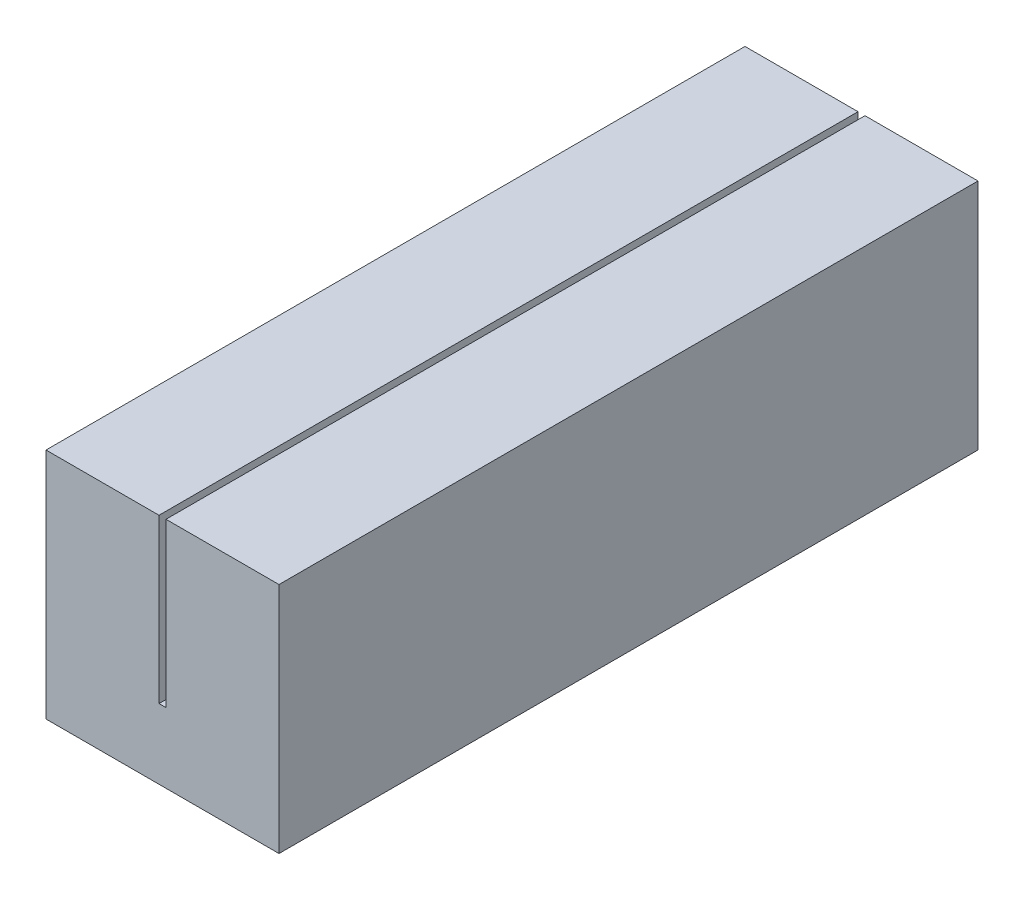
SolidWorks part; units mm, degrees
ref_plane "Front Plane" through (0, 0, 0) normal (0, 0, 1) x (1, 0, 0)
ref_plane "Top Plane" through (0, 0, 0) normal (0, 1, 0) x (1, 0, 0)
ref_plane "Right Plane" through (0, 0, 0) normal (1, 0, 0) x (0, 0, -1)
sketch "Sketch1" plane through (0, 0, 0) normal (0, 0, 1) x (1, 0, 0)
  line L0 (-0.15, 5) -> (-0.15, -2)
  line L1 (-5, 5) -> (-0.15, 5)
  line L2 (-5, 5) -> (-5, -5)
  line L3 (-5, -5) -> (5, -5)
  line L4 (5, 5) -> (5, -5)
  line L5 (-5, 5) -> (5, -5) construction
  line L6 (-5, -5) -> (5, 5) construction
  line L7 (-0.15, -2) -> (0.15, -2)
  line L8 (0.15, -2) -> (0.15, 5)
  line L9 (0.15, 5) -> (5, 5)
  point P0 (0, 0)
  point P8 (0, -2)
  dimension "D1" = 10
  dimension "D2" = 10
  dimension "D3" = 0.3
  dimension "D4" = 7
extrude "Boss-Extrude1" add sketch "Sketch1" along normal mid plane 30
